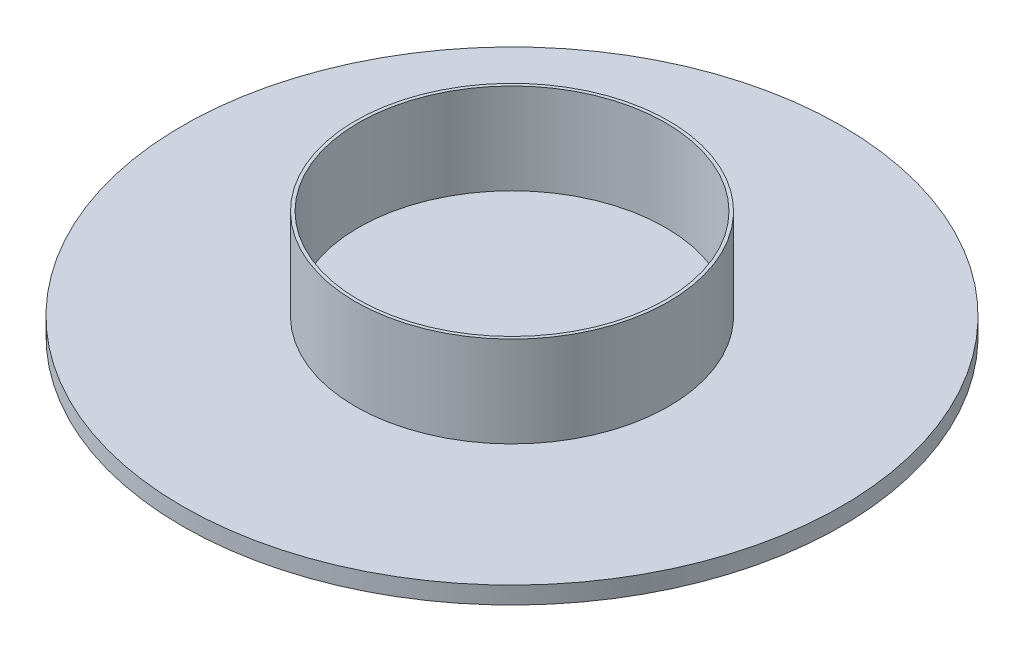
SolidWorks part; units mm, degrees
ref_plane "정면" through (0, 0, 0) normal (0, 0, 1) x (1, 0, 0)
ref_plane "윗면" through (0, 0, 0) normal (0, 1, 0) x (1, 0, 0)
ref_plane "우측면" through (0, 0, 0) normal (1, 0, 0) x (0, 0, -1)
sketch "스케치1" plane through (0, 0, 0) normal (0, 1, 0) x (1, 0, 0)
  circle A0 centre (0, 0) radius 30.5
  dimension "D1" = 61
extrude "보스-돌출1" add sketch "스케치1" along normal blind 1.6
sketch "스케치2" plane through (0, 0, 0) normal (0, 1, 0) x (1, 0, 0)
  circle A0 centre (0, 0) radius 14.5
  circle A1 centre (0, 0) radius 14.2
  dimension "D1" = 28.4
  dimension "D2" = 29
extrude "보스-돌출2" add sketch "스케치2" along normal blind 10
sketch "스케치3" plane through (0, 0, 0) normal (0, 1, 0) x (1, 0, 0)
  circle A0 centre (0, 0) radius 14.2
  circle A1 centre (0, 0) radius 17.7
  dimension "D1" = 28.4
  dimension "D2" = 35.4
extrude "보스-돌출3" add sketch "스케치3" against normal blind 0.8 separate body
